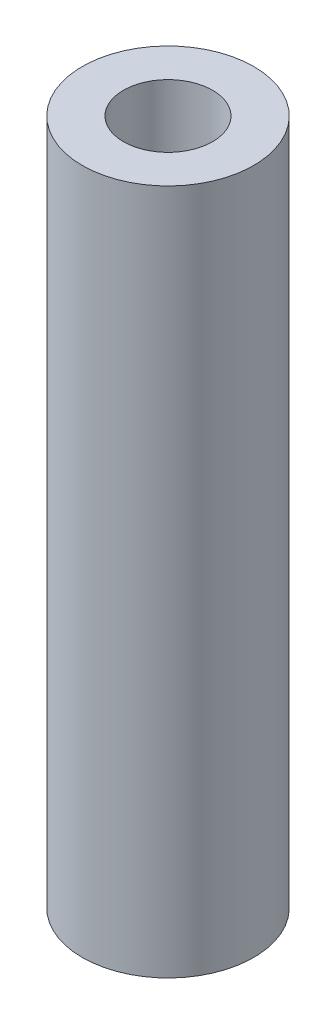
SolidWorks part; units mm, degrees
material "6061-T6 (SS)"
ref_plane "Front" through (0, 0, 0) normal (0, 0, 1) x (1, 0, 0)
ref_plane "Top" through (0, 0, 0) normal (0, 1, 0) x (1, 0, 0)
ref_plane "Right" through (0, 0, 0) normal (1, 0, 0) x (0, 0, -1)
sketch "Sketch1" plane through (0, 0, 0) normal (0, 1, 0) x (1, 0, 0)
  circle A0 centre (0, 0) radius 6.35
  circle A1 centre (0, 0) radius 3.302
  dimension "D1" = 12.7
  dimension "D2" = 3.048
  dimension "D3" = 6.604
extrude "Boss-Extrude1" add sketch "Sketch1" along normal mid plane 50.8
